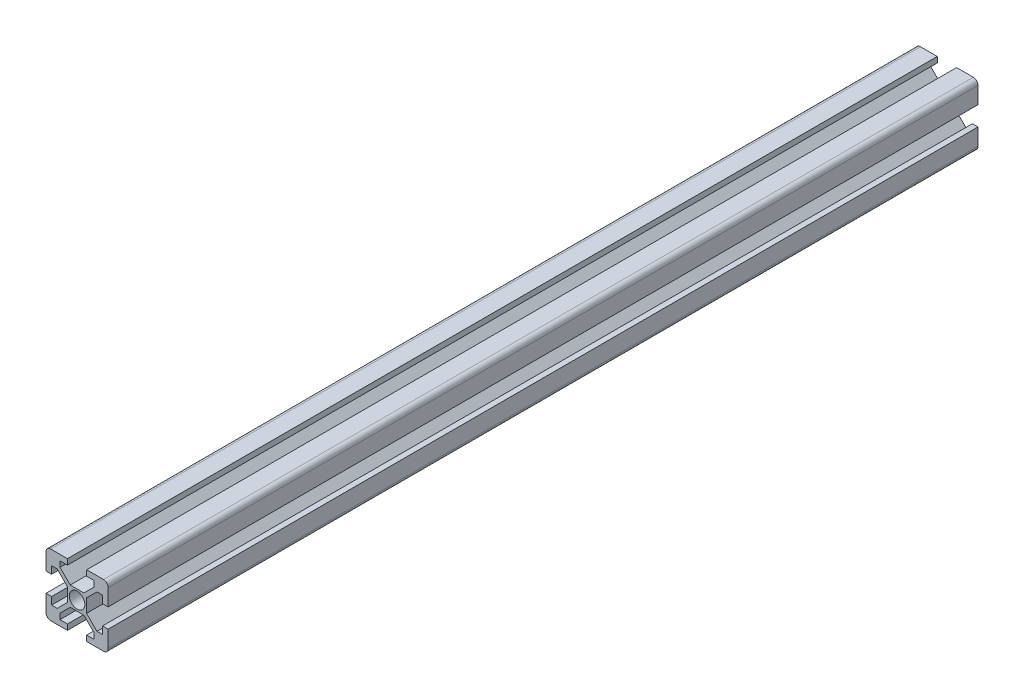
SolidWorks part; units mm, degrees
ref_plane "前视基准面" through (0, 0, 0) normal (0, 0, 1) x (1, 0, 0)
ref_plane "上视基准面" through (0, 0, 0) normal (0, 1, 0) x (1, 0, 0)
ref_plane "右视基准面" through (0, 0, 0) normal (1, 0, 0) x (0, 0, -1)
sketch "草图1" plane through (0, 0, 0) normal (0, 0, 1) x (1, 0, 0)
  line L0 (-10, -3.1) -> (-8.2, -3.1)
  line L1 (-8.5, 10) -> (8.5, 10)
  line L2 (-10, 8.5) -> (-10, -8.5)
  line L3 (-8.5, -10) -> (8.5, -10)
  line L4 (10, 8.5) -> (10, -8.5)
  line L5 (-10, 10) -> (10, -10) construction
  line L6 (-10, -10) -> (10, 10) construction
  line L7 (-3.0541, 3.1) -> (3.0541, 3.1)
  line L8 (-3.0541, 3.1) -> (-3.0541, -3.1)
  line L9 (-3.0541, -3.1) -> (3.0541, -3.1)
  line L10 (3.0541, 3.1) -> (3.0541, -3.1)
  line L11 (-3.0541, 3.1) -> (3.0541, -3.1) construction
  line L12 (-3.0541, -3.1) -> (3.0541, 3.1) construction
  line L13 (-8.2, -3.1) -> (-8.2, -5.5)
  line L14 (-8.2, -5.5) -> (-6.3971, -5.5)
  line L15 (-6.3971, -5.5) -> (-3.0541, -2.1571)
  line L16 (-5.5, 6.3971) -> (-2.1571, 3.0541)
  line L17 (-5.5, 8.2) -> (-5.5, 6.3971)
  line L18 (-3.1, 8.2) -> (-5.5, 8.2)
  line L19 (-3.1, 10) -> (-3.1, 8.2)
  line L20 (6.3971, 5.5) -> (3.0541, 2.1571)
  line L21 (8.2, 5.5) -> (6.3971, 5.5)
  line L22 (8.2, 3.1) -> (8.2, 5.5)
  line L23 (10, 3.1) -> (8.2, 3.1)
  line L24 (5.5, -6.3971) -> (2.1571, -3.0541)
  line L25 (5.5, -8.2) -> (5.5, -6.3971)
  line L26 (3.1, -8.2) -> (5.5, -8.2)
  line L27 (3.1, -10) -> (3.1, -8.2)
  line L28 (-3.1, -10) -> (-3.1, -8.2)
  line L29 (-3.1, -8.2) -> (-5.5, -8.2)
  line L30 (-5.5, -8.2) -> (-5.5, -6.3971)
  line L31 (-5.5, -6.3971) -> (-2.1571, -3.0541)
  line L32 (-8.2, 5.5) -> (-6.3971, 5.5)
  line L33 (-6.3971, 5.5) -> (-3.0541, 2.1571)
  line L34 (-8.2, 3.1) -> (-8.2, 5.5)
  line L35 (-10, 3.1) -> (-8.2, 3.1)
  line L36 (5.5, 8.2) -> (5.5, 6.3971)
  line L37 (5.5, 6.3971) -> (2.1571, 3.0541)
  line L38 (3.1, 8.2) -> (5.5, 8.2)
  line L39 (3.1, 10) -> (3.1, 8.2)
  line L40 (8.2, -5.5) -> (6.3971, -5.5)
  line L41 (6.3971, -5.5) -> (3.0541, -2.1571)
  line L42 (8.2, -3.1) -> (8.2, -5.5)
  line L43 (10, -3.1) -> (8.2, -3.1)
  circle A0 centre (0, 0) radius 2.5
  arc A1 (-10, 8.5) -> (-8.5, 10) centre (-8.5, 8.5) cw
  arc A2 (-10, -8.5) -> (-8.5, -10) centre (-8.5, -8.5) ccw
  arc A3 (8.5, 10) -> (10, 8.5) centre (8.5, 8.5) cw
  arc A4 (10, -8.5) -> (8.5, -10) centre (8.5, -8.5) cw
  point P0 (0, 0)
  point P20 (0, 0)
  point P26 (0, 0)
  point P32 (0, 0)
  point P38 (0, 0)
  point P60 (0, 0)
  dimension "D1" = 4
  dimension "D3" = 1.5
  dimension "D4" = 1.5
  dimension "D5" = 1.5
  dimension "D2" = 4
extrude "凸台-拉伸1" add sketch "草图1" along normal blind 280
